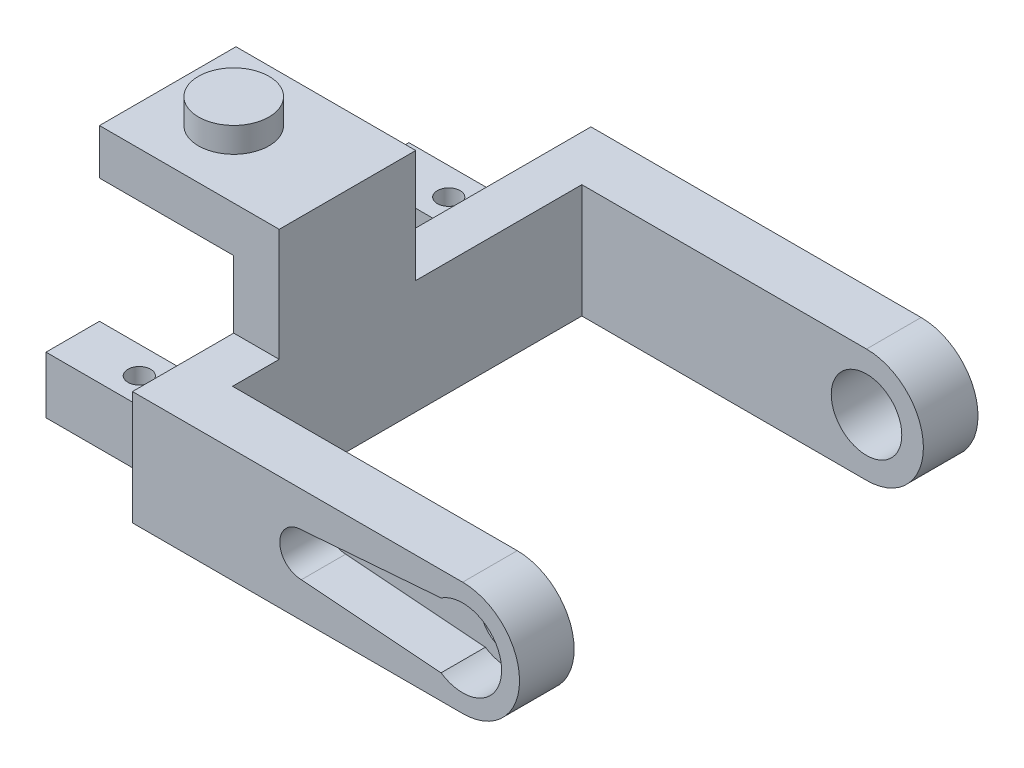
SolidWorks part; units mm, degrees
ref_plane "Front Plane" through (0, 0, 0) normal (0, 0, 1) x (1, 0, 0)
ref_plane "Top Plane" through (0, 0, 0) normal (0, 1, 0) x (1, 0, 0)
ref_plane "Right Plane" through (0, 0, 0) normal (1, 0, 0) x (0, 0, -1)
sketch "Sketch1" plane through (0, 0, 0) normal (0, 0, 1) x (1, 0, 0)
  line L0 (-27.0233, 0) -> (27.0233, 0) construction
  line L1 (-27.0233, 5) -> (27.0233, 5)
  line L2 (-27.0233, -5) -> (27.0233, -5)
  arc A0 (-27.0233, 5) -> (-27.0233, -5) centre (-27.0233, 0) ccw
  arc A1 (27.0233, -5) -> (27.0233, 5) centre (27.0233, 0) ccw
  point P2 (0, 0)
  point P8 (32.0233, 0)
  dimension "D1" = 5
  dimension "D2" = 54.0465
extrude "Boss-Extrude1" add sketch "Sketch1" along normal mid plane 40.3
sketch "Sketch2" plane through (0, 5, 0) normal (0, 1, 0) x (1, 0, 0)
  line L0 (-2, -20.15) -> (-2, 20.15)
  line L1 (0, 0) -> (7.8559, 0) construction
  line L2 (-27.0233, -20.15) -> (-37.952, -20.15)
  line L4 (27.0233, 20.15) -> (-27.0233, 20.15) construction
  line L5 (-37.952, -20.15) -> (-37.952, 20.15)
  line L6 (-37.952, 20.15) -> (-27.0233, 20.15)
  line L7 (27.0233, 20.15) -> (-27.0233, 20.15)
  line L13 (27.0233, 15.35) -> (38.0583, 15.35)
  line L14 (27.0233, -15.35) -> (38.0583, -15.35)
  line L15 (38.0583, -15.35) -> (38.0583, 15.35)
  line L22 (2, -15.35) -> (27.0233, -15.35)
  line L23 (2, 15.35) -> (2, -15.35)
  line L24 (27.0233, 15.35) -> (2, 15.35)
  line L25 (27.0233, -20.15) -> (27.0233, 20.15)
  line L26 (-27.0233, -20.15) -> (27.0233, -20.15)
  line L27 (-27.0233, 20.15) -> (-27.0233, -20.15)
  line L28 (-2, 20.15) -> (-27.0233, 20.15)
  line L30 (-27.0233, -20.15) -> (-2, -20.15)
  point P10 (0, 0)
  dimension "D1" = 4.8
  dimension "D3" = 2
  dimension "D4" = 2
  dimension "D2" = 0
extrude "Cut-Extrude1" cut sketch "Sketch2" against normal through all both and the other way through all
sketch "Sketch4" plane through (0, 0, 20.15) normal (0, 0, 1) x (1, 0, 0)
  line L0 (-27.0233, 0) -> (27.0233, 0) construction
  line L2 (25.1237, 2.85) -> (12.8483, 1.9)
  line L3 (12.8483, -1.9) -> (25.1237, -2.85)
  line L4 (0, 0) -> (0, 10.0499) construction
  line L7 (0, 0) -> (27.0233, 0) construction
  arc A0 (25.1237, -2.85) -> (25.1237, 2.85) centre (27.0233, 0) ccw
  arc A1 (12.8483, 1.9) -> (12.8483, -1.9) centre (12.8483, 0) ccw
  circle A5 centre (27.0233, 0) radius 2.3 construction
  point P3 (12.8483, 0)
  point P6 (25.1237, 2.85)
  point P7 (25.1237, -2.85)
  point P12 (0, 0)
  dimension "D1" = 6.85
  dimension "D3" = 3.8
  dimension "D2" = 14.175
  dimension "D4" = 5.7
extrude "Cut-Extrude2" cut sketch "Sketch4" against normal blind 3.9
sketch "Sketch5" plane through (0, 0, 0) normal (0, 0, 1) x (1, 0, 0)
  circle A0 centre (27.0233, 0) radius 2.3 construction
  circle A2 centre (27.0233, 0) radius 2.3
extrude "Cut-Extrude6" cut sketch "Sketch5" along normal through all
sketch "Sketch6" plane through (0, 0, 0) normal (0, 0, 1) x (1, 0, 0)
  circle A0 centre (27.0233, 0) radius 3.1
  dimension "D1" = 6.2
extrude "Cut-Extrude7" cut sketch "Sketch6" against normal through all
sketch "Sketch7" plane through (0, 0, 0) normal (0, 1, 0) x (1, 0, 0)
  line L0 (0, 0) -> (-11.5871, 0) construction
  line L1 (-2, 15.95) -> (-13.8, 15.95)
  line L2 (-2, 20.15) -> (-2, -20.15) construction
  line L3 (-13.8, 15.95) -> (-13.8, 11.25)
  line L4 (-13.8, 11.25) -> (-2, 11.25)
  line L5 (-2, 11.25) -> (-2, 15.95)
  line L6 (-13.8, -11.25) -> (-2, -11.25)
  line L7 (-13.8, -15.95) -> (-13.8, -11.25)
  line L8 (-2, -15.95) -> (-13.8, -15.95)
  line L9 (-2, -11.25) -> (-2, -15.95)
  circle A0 centre (-7.9, -13.65) radius 1
  circle A2 centre (-7.9, 13.55) radius 1
  point P13 (-7.9, -13.65)
  point P20 (32.1761, 13.9943)
  dimension "D6" = 2
  dimension "D1" = 11.8
  dimension "D2" = 4.7
  dimension "D3" = 22.5
  dimension "D4" = 2.3
  dimension "D5" = 5.9
  dimension "D7" = 2.3
  dimension "D8" = 5.9
extrude "Boss-Extrude2" add sketch "Sketch7" against normal up to surface (5 mm away) up to face at (13.5116, -5, 0)
sketch "Sketch8" plane through (0, 5, 0) normal (0, 1, 0) x (1, 0, 0)
  line L2 (-2, 0.75) -> (2, 0.75)
  line L3 (-2, -11.25) -> (2, -11.25)
  line L8 (27.0233, 20.15) -> (-2, 20.15)
  line L9 (-2, 20.15) -> (-2, -20.15)
  line L10 (-2, -20.15) -> (27.0233, -20.15)
  line L11 (27.0233, -20.15) -> (27.0233, -15.35)
  line L12 (27.0233, -15.35) -> (2, -15.35)
  line L13 (2, -15.35) -> (2, 15.35)
  line L14 (2, 15.35) -> (27.0233, 15.35)
  line L15 (27.0233, 15.35) -> (27.0233, 20.15)
  line L17 (-2, 0.75) -> (-2, -11.25)
  line L21 (2, -11.25) -> (2, 0.75)
  dimension "D2" = 12
  dimension "D1" = 0
extrude "Boss-Extrude3" add sketch "Sketch8" along normal blind 9.9
sketch "Sketch9" plane through (0, 14.9, 0) normal (0, 1, 0) x (1, 0, 0)
  line L0 (-2, 0.75) -> (-13.8, 0.75)
  line L1 (-13.8, 0.75) -> (-13.8, -11.25)
  line L2 (-2, -11.25) -> (-13.8, -11.25) construction
  line L3 (-2, -11.25) -> (-13.8, -11.25)
  line L4 (-2, 0.75) -> (-2, -11.25)
  line L5 (-2, -11.25) -> (2, -11.25)
  line L6 (2, -11.25) -> (2, 0.75)
  line L7 (2, 0.75) -> (-2, 0.75)
  line L8 (-2, 0.75) -> (-2, -11.25)
  circle A0 centre (-7.8992, -5.35) radius 3.1 construction
  point P2 (-7.8992, -5.35)
  point P4 (-2, -5.25)
  point P11 (0, 0)
  dimension "D4" = 6.2
  dimension "D2" = 5.9
  dimension "D3" = 5.9
  dimension "D1" = 0
extrude "Boss-Extrude4" add sketch "Sketch9" against normal blind 4
sketch "Sketch10" plane through (0, 14.9, 0) normal (0, 1, 0) x (1, 0, 0)
  circle A0 centre (-7.8992, -5.35) radius 3.1 construction
  circle A1 centre (-7.8992, -5.35) radius 3.1
extrude "Boss-Extrude5" add sketch "Sketch10" along normal blind 2.2
equation "\"D4@Sketch2\"=\"D3@Sketch2\""
